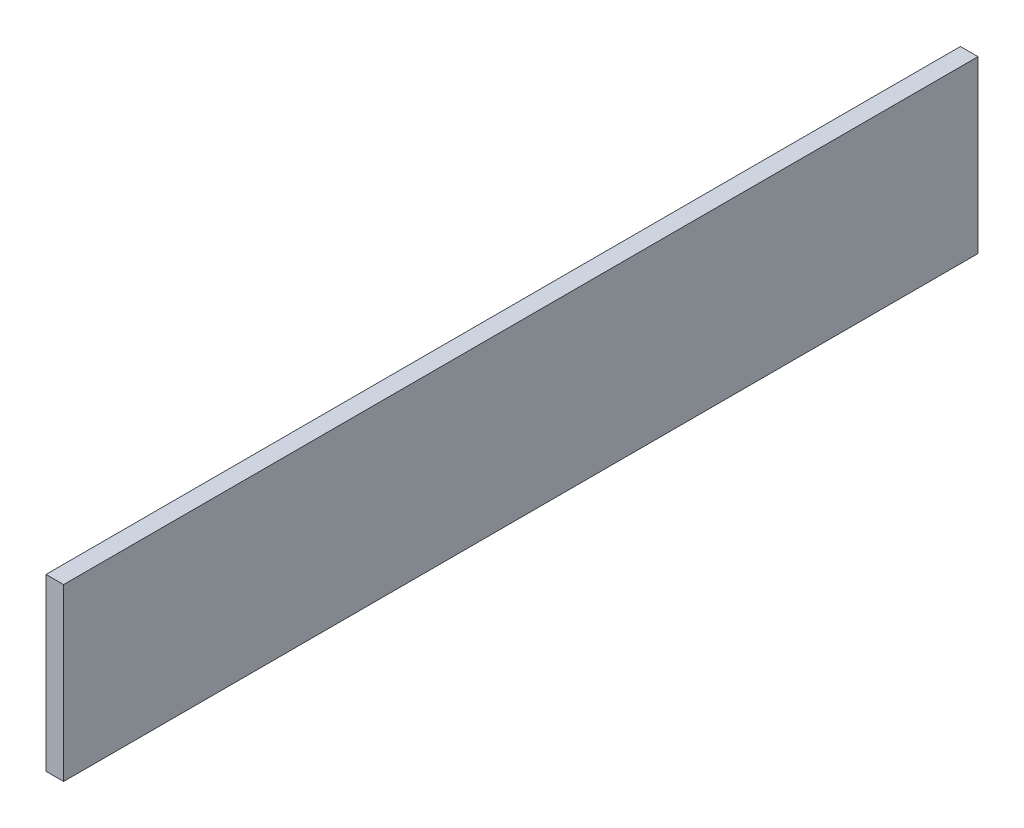
SolidWorks part; units mm, degrees
ref_plane "Alzado" through (0, 0, 0) normal (0, 0, 1) x (1, 0, 0)
ref_plane "Planta" through (0, 0, 0) normal (0, 1, 0) x (1, 0, 0)
ref_plane "Vista lateral" through (0, 0, 0) normal (1, 0, 0) x (0, 0, -1)
sketch "Croquis1" plane through (0, 0, 0) normal (1, 0, 0) x (0, 0, -1)
  line L1 (165, -30.775) -> (-165, -30.775)
  line L2 (165, -30.775) -> (165, 30.775)
  line L3 (165, 30.775) -> (-165, 30.775)
  line L4 (-165, -30.775) -> (-165, 30.775)
  line L5 (165, -30.775) -> (-165, 30.775) construction
  line L6 (165, 30.775) -> (-165, -30.775) construction
  point P1 (0, 0)
  dimension "D1" = 61.55
  dimension "D2" = 330
extrude "Saliente-Extruir2" add sketch "Croquis1" along normal blind 6.35
